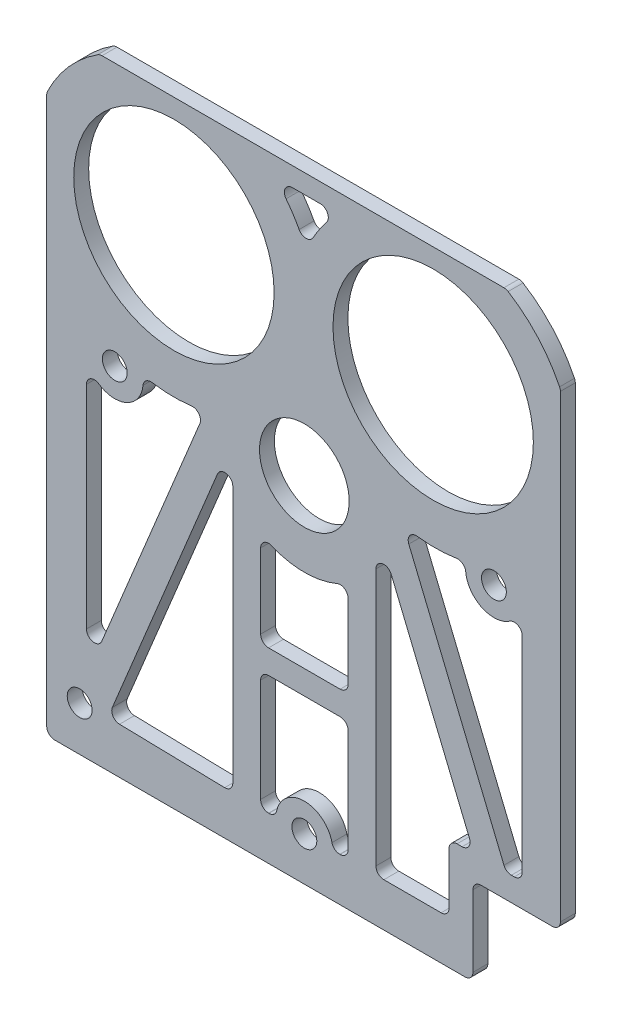
SolidWorks part; units mm, degrees
material "6061 Alloy"
ref_plane "Front Plane" through (0, 0, 0) normal (0, 0, 1) x (1, 0, 0)
ref_plane "Top Plane" through (0, 0, 0) normal (0, 1, 0) x (1, 0, 0)
ref_plane "Right Plane" through (0, 0, 0) normal (1, 0, 0) x (0, 0, -1)
sketch "Sketch2" plane through (0, 0, 0) normal (0, 0, 1) x (1, 0, 0)
  line L0 (-119.1604, -45.5202) -> (-119.1604, -76.6318)
  line L1 (-161.6655, 75.7682) -> (-31.8307, 75.7682)
  line L2 (-178.604, 56.6882) -> (-178.604, -121.1118)
  line L3 (-178.604, -121.1118) -> (-14.5124, -121.1118)
  line L4 (-14.5124, 56.6882) -> (-14.5124, -121.1118)
  line L5 (-73.4404, -45.5202) -> (-73.4404, -76.6318)
  line L6 (-165.904, -8.0518) -> (-165.904, -72.2342)
  line L7 (-73.4404, -45.5202) -> (-73.4404, -9.6665)
  line L8 (-119.1604, -45.5202) -> (-119.1604, -9.6665)
  line L9 (-26.6968, -8.0518) -> (-26.6968, -72.2342)
  line L10 (-96.3004, -27.3085) -> (-96.3004, -76.6318) construction
  line L11 (-165.904, -72.2342) -> (-165.904, -98.126)
  line L12 (-110.2704, -107.1748) -> (-105.3491, -107.1748)
  line L13 (-119.1604, -107.1997) -> (-119.1604, -76.6318)
  line L14 (-73.4404, -76.6318) -> (-73.4404, -107.1748)
  line L15 (-73.4404, -107.1748) -> (-50.0686, -107.1748)
  line L16 (-26.6968, -85.5616) -> (-26.6968, -72.2342)
  line L17 (-105.7518, 69.6722) -> (-85.4178, 69.6722)
  line L18 (-110.2704, -30.9118) -> (-110.2704, -61.4548)
  line L19 (-110.2704, -61.4548) -> (-82.3304, -61.4548)
  line L20 (-82.3304, -30.9118) -> (-82.3304, -61.4548)
  line L21 (-159.0493, -106.298) -> (-119.1604, -107.1997)
  line L22 (-82.3304, -107.1748) -> (-82.3304, -69.0748)
  line L23 (-165.904, -98.126) -> (-127.8994, -6.0591)
  line L24 (-110.2704, -107.1748) -> (-110.2704, -69.0748)
  line L25 (-82.3304, -69.0748) -> (-110.2704, -69.0748)
  line L26 (-87.2516, -107.1748) -> (-82.3304, -107.1748)
  line L27 (-73.4404, -9.6665) -> (-42.1114, -85.5616)
  line L28 (-26.6968, -85.5616) -> (-31.8833, -85.5616)
  line L29 (-50.0686, -107.1748) -> (-50.0686, -85.5616)
  line L30 (-119.1604, -9.6665) -> (-159.0493, -106.298)
  line L31 (-31.8833, -85.5616) -> (-64.7014, -6.0591)
  line L32 (-42.1114, -85.5616) -> (-50.0686, -85.5616)
  circle A0 centre (-137.964, 37.6682) radius 32.004
  circle A1 centre (-55.1524, 37.6682) radius 32.004
  circle A2 centre (-96.3004, -8.0518) radius 14.3263
  arc A3 (-44.5721, -6.0591) -> (-64.7014, -6.0591) centre (-54.6368, 37.6682) cw
  arc A4 (-26.6968, -8.0518) -> (-44.5721, -6.0591) centre (-35.7455, -8.0518) cw
  arc A5 (-110.2704, -30.9118) -> (-82.3304, -30.9118) centre (-96.3004, -8.0518) ccw
  arc A6 (-95.7594, 54.421) -> (-105.7518, 69.6722) centre (-137.964, 37.6682) ccw
  circle A7 centre (-35.7455, -8.0518) radius 3.9687
  circle A8 centre (-156.8553, -8.0518) radius 3.9687
  arc A9 (-85.4178, 69.6722) -> (-95.7594, 54.421) centre (-54.6368, 37.6682) ccw
  arc A10 (-165.904, -8.0518) -> (-148.0287, -6.0591) centre (-156.8553, -8.0518) ccw
  arc A11 (-161.6655, 75.7682) -> (-178.604, 56.6882) centre (-137.964, 37.6682) ccw
  circle A12 centre (-168.0773, -106.9099) radius 3.9687
  arc A13 (-148.0287, -6.0591) -> (-127.8994, -6.0591) centre (-137.964, 37.6682) ccw
  circle A15 centre (-96.3004, -107.1748) radius 3.9687
  arc A16 (-87.2516, -107.1748) -> (-105.3491, -107.1748) centre (-96.3004, -107.1748) ccw
  arc A17 (-14.5124, 56.6882) -> (-31.8307, 75.7682) centre (-54.6368, 37.6682) ccw
  dimension "D1" = 64.008
  dimension "D2" = 64.008
  dimension "D15" = 7.9375
  dimension "D16" = 5.08
  dimension "D21" = 5.08
  dimension "D9" = 9.0488
  dimension "D19" = 7.9375
  dimension "D20" = 38.1
  dimension "D18" = 7.9375
  dimension "D3" = 82.8116
  dimension "D4" = 45.72
  dimension "D5" = 41.148
  dimension "D6" = 38.1
  dimension "D7" = 40.64
  dimension "D8" = 40.64
  dimension "D10" = 12.7
  dimension "D11" = 177.8
  dimension "D12" = 22.86
  dimension "D13" = 177.8
  dimension "D14" = 8.89
  dimension "D17" = 7.62
  dimension "D22" = 180
extrude "Boss-Extrude3" add sketch "Sketch2" along normal blind 4.7625
fillet "Fillet2" radius 2.54 6 edges at (-26.6968, -8.0518, 2.3813) (-44.5721, -6.0591, 2.3813) (-82.3304, -30.9118, 2.3813) (-110.2704, -30.9118, 2.3813) (-148.0287, -6.0591, 2.3813) (-165.904, -8.0518, 2.3813)
fillet "Fillet3" radius 2.54 10 edges at (-26.6968, -85.5616, 2.3813) (-73.4404, -107.1748, 2.3813) (-87.2516, -107.1748, 2.3813) (-110.2704, -61.4548, 2.3813) (-110.2704, -107.1748, 2.3813) (-119.1604, -107.1997, 2.3813) (-82.3304, -61.4548, 2.3813) (-50.0686, -107.1748, 2.3813) (-82.3304, -107.1748, 2.3813) (-105.3491, -107.1748, 2.3813)
fillet "Fillet4" radius 2.54 2 edges at (-110.2704, -69.0748, 2.3813) (-82.3304, -69.0748, 2.3813)
fillet "Fillet5" radius 2.54 3 edges at (-105.7518, 69.6722, 2.3813) (-85.4178, 69.6722, 2.3813) (-95.7594, 54.421, 2.3813)
sketch "Sketch3" plane through (0, 0, 4.7625) normal (0, 0, 1) x (1, 0, 0)
  line L0 (-31.8833, -85.5616) -> (-29.2368, -85.5616) construction
  line L1 (-14.5124, -121.1118) -> (-42.4486, -121.1118)
  line L2 (-14.5124, -121.1118) -> (-14.5124, -93.1816)
  line L3 (-14.5124, -93.1816) -> (-42.4486, -93.1816)
  line L4 (-42.4486, -121.1118) -> (-42.4486, -93.1816)
  line L5 (-50.0686, -104.6348) -> (-50.0686, -85.5616) construction
  dimension "D1" = 7.62
  dimension "D2" = 7.62
extrude "Cut-Extrude1" cut sketch "Sketch3" against normal blind 4.7625
fillet "Fillet6" radius 2.54 8 edges at (-178.604, -121.1118, 2.3813) (-42.4486, -93.1816, 2.3813) (-42.4486, -121.1118, 2.3813) (-14.5124, -93.1816, 2.3813) (-14.5124, 56.6882, 2.3813) (-31.8307, 75.7682, 2.3813) (-178.604, 56.6882, 2.3813) (-161.6655, 75.7682, 2.3813)
fillet "Fillet7" radius 2.54 9 edges at (-31.8833, -85.5616, 2.3813) (-165.904, -98.126, 2.3813) (-159.0493, -106.298, 2.3813) (-64.7014, -6.0591, 2.3813) (-73.4404, -9.6665, 2.3813) (-119.1604, -9.6665, 2.3813) (-127.8994, -6.0591, 2.3813) (-42.1114, -85.5616, 2.3813) (-50.0686, -85.5616, 2.3813)
